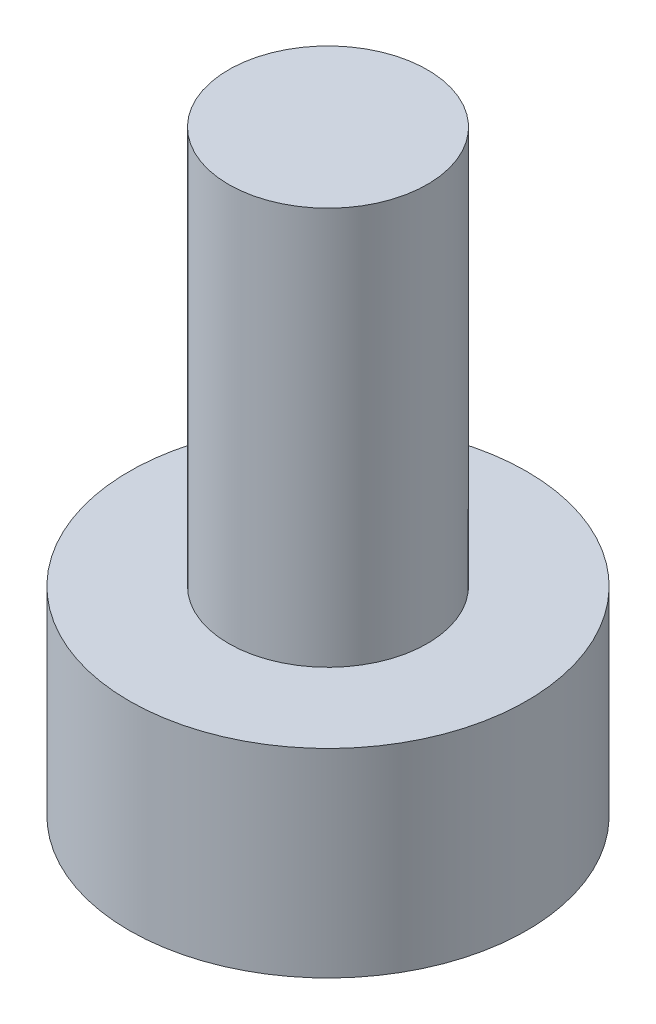
SolidWorks part; units mm, degrees
ref_plane "前视基准面" through (0, 0, 0) normal (0, 0, 1) x (1, 0, 0)
ref_plane "上视基准面" through (0, 0, 0) normal (0, 1, 0) x (1, 0, 0)
ref_plane "右视基准面" through (0, 0, 0) normal (1, 0, 0) x (0, 0, -1)
sketch "草图2" plane through (0, 0, 0) normal (0, 1, 0) x (1, 0, 0)
  circle A0 centre (0, 0) radius 3
  dimension "D1" = 6
extrude "凸台-拉伸1" add sketch "草图2" along normal blind 3
sketch "草图3" plane through (0, 3, 0) normal (0, 1, 0) x (1, 0, 0)
  circle A0 centre (0, 0) radius 1.5
  dimension "D1" = 3
extrude "凸台-拉伸2" add sketch "草图3" along normal blind 6
